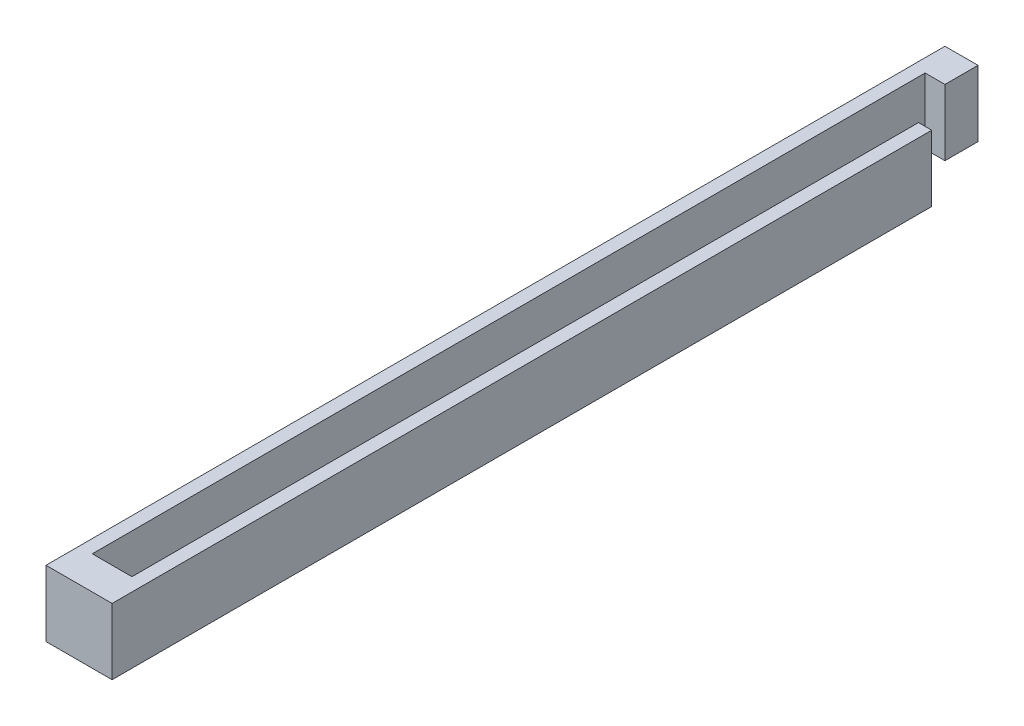
SolidWorks part; units mm, degrees
ref_plane "Front Plane" through (0, 0, 0) normal (0, 0, 1) x (1, 0, 0)
ref_plane "Top Plane" through (0, 0, 0) normal (0, 1, 0) x (1, 0, 0)
ref_plane "Right Plane" through (0, 0, 0) normal (1, 0, 0) x (0, 0, -1)
sketch "Sketch1" plane through (0, 0, 0) normal (0, 1, 0) x (1, 0, 0)
  line L1 (5, -68) -> (-5, -68)
  line L2 (5, -68) -> (5, 68)
  line L3 (5, 68) -> (-5, 68)
  line L4 (-5, -68) -> (-5, 68)
  line L5 (5, -68) -> (-5, 68) construction
  line L6 (5, 68) -> (-5, -68) construction
  point P0 (0, 0)
  dimension "D1" = 10
  dimension "D2" = 136
extrude "Boss-Extrude1" add sketch "Sketch1" along normal blind 10
sketch "Sketch2" plane through (0, 0, 0) normal (0, 1, 0) x (1, 0, 0)
  line L1 (0, -63) -> (-3, -63)
  line L2 (3, -63) -> (3, 63)
  line L3 (0, 63) -> (-3, 63)
  line L4 (-3, -63) -> (-3, 63)
  line L5 (3, -63) -> (-3, 63) construction
  line L6 (3, 63) -> (-3, -63) construction
  line L11 (0, -63) -> (3, -63)
  line L12 (5, 68) -> (-5, 68) construction
  line L14 (3, 63) -> (3, 68)
  line L15 (3, 68) -> (0, 68)
  line L16 (0, 63) -> (0, 68)
  point P0 (0, 0)
  dimension "D1" = 6
  dimension "D2" = 126
  dimension "D3" = 3
extrude "Cut-Extrude1" cut sketch "Sketch2" along normal blind 10
ref_plane "Plane1" through (0, 10, 0) normal (0, 1, 0) x (1, 0, 0)
sketch "Sketch4" plane through (0, 10, 0) normal (0, 1, 0) x (1, 0, 0)
  line L0 (5, -68) -> (5, 68) construction
  line L1 (3, 68) -> (5, 68)
  line L2 (3, 68) -> (3, 56)
  line L3 (3, 56) -> (5, 56)
  line L4 (5, 68) -> (5, 56)
  dimension "D1" = 12
extrude "Cut-Extrude3" cut sketch "Sketch4" against normal blind 10
